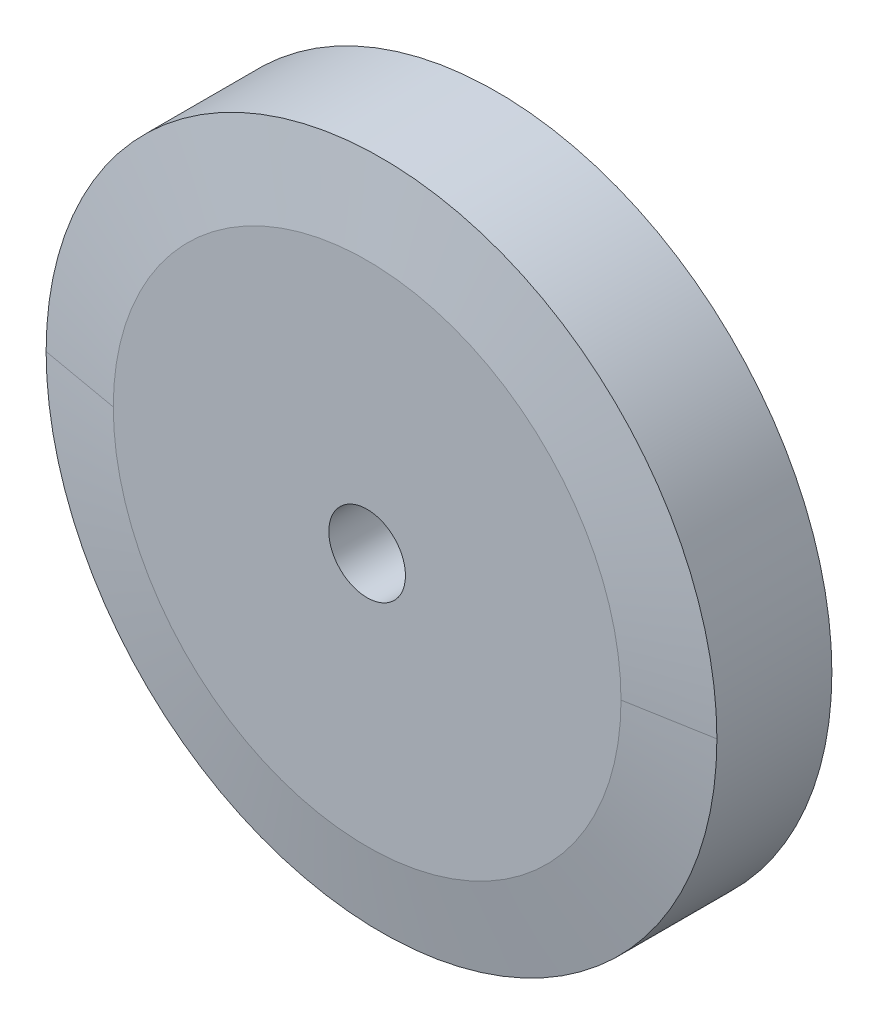
SolidWorks part; units mm, degrees
material "1.0725 (15SMn13)"
ref_plane "정면" through (0, 0, 0) normal (0, 0, 1) x (1, 0, 0)
ref_plane "윗면" through (0, 0, 0) normal (0, 1, 0) x (1, 0, 0)
ref_plane "우측면" through (0, 0, 0) normal (1, 0, 0) x (0, 0, -1)
sketch "스케치2" plane through (0, 0, 0) normal (0, 0, 1) x (1, 0, 0)
  circle A0 centre (0, 0) radius 35
  dimension "D1" = 70
extrude "보스-돌출1" add sketch "스케치2" along normal blind 15
ref_plane "평면1" through (0, 0, 8) normal (0, 0, 1) x (1, 0, 0)
sketch "스케치5" plane through (0, 0, 15) normal (0, 0, 1) x (1, 0, 0)
  circle A0 centre (0, 0) radius 4
  dimension "D1" = 8
extrude "컷-돌출1" cut sketch "스케치5" against normal blind 20 contours A0
sketch "스케치4" plane through (0, 0, 0) normal (0, 1, 0) x (1, 0, 0)
  line L0 (-35, -1.5) -> (-26.4931, 0)
  line L2 (-26.4931, 0) -> (-35, 0)
  line L3 (-35, 0) -> (-35, -1.5)
  line L5 (-35, 0) -> (-35, -15) construction
  line L6 (35, 0) -> (-35, 0) construction
  line L7 (-35, -15) -> (-26.4931, -15)
  line L8 (-35, -15) -> (35, -15) construction
  line L9 (-26.4931, -15) -> (-35, -13.5)
  line L10 (-35, 0) -> (-35, -15) construction
  line L11 (-35, -13.5) -> (-35, -15)
  dimension "D1" = 80
  dimension "D2" = 80
  dimension "D3" = 1.5
  dimension "D4" = 1.5
sweep "컷-스윕2" cut profiles "스케치4" path edge at (35, 0, 0)
